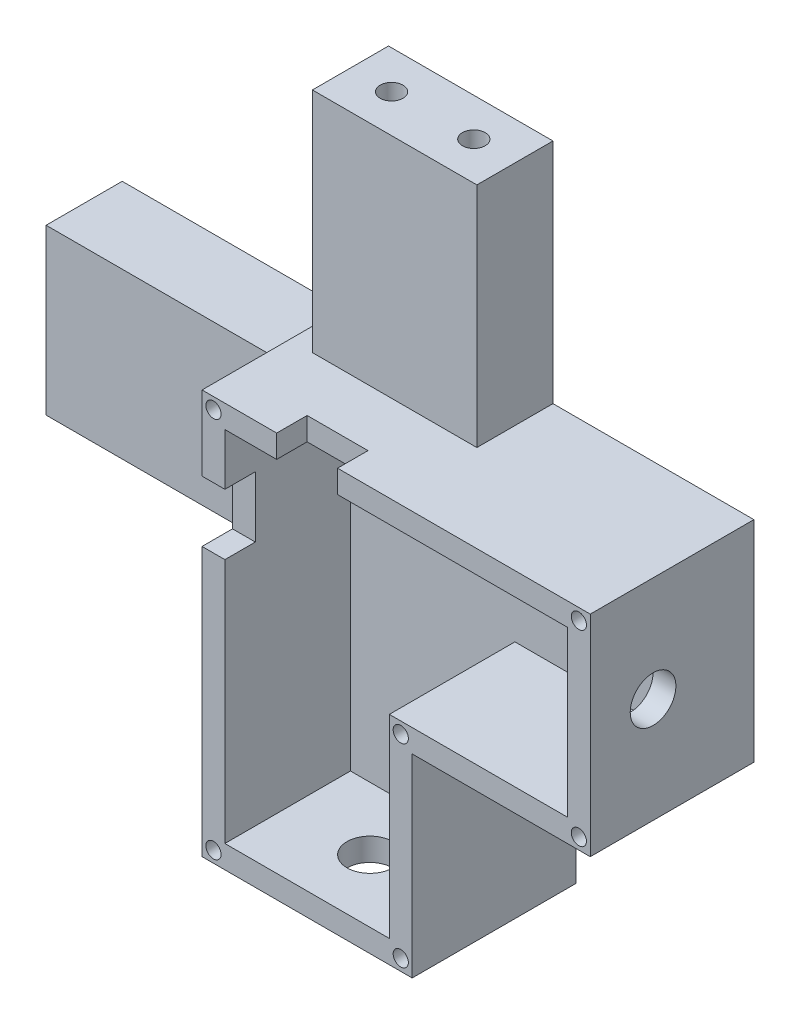
SolidWorks part; units mm, degrees
ref_plane "Plan de face" through (0, 0, 0) normal (0, 0, 1) x (1, 0, 0)
ref_plane "Plan de dessus" through (0, 0, 0) normal (0, 1, 0) x (1, 0, 0)
ref_plane "Plan de droite" through (0, 0, 0) normal (1, 0, 0) x (0, 0, -1)
sketch "Esquisse1" plane through (0, 0, 0) normal (0, 0, 1) x (1, 0, 0)
  line L1 (0, 0) -> (-80, 0)
  line L2 (0, 0) -> (0, 21.61)
  line L3 (0, 21.61) -> (-80, 21.61)
  line L4 (-80, 0) -> (-80, 21.61)
  line L5 (-45.01, 21.61) -> (-23.4, 21.61)
  line L6 (-45.01, 21.61) -> (-45.01, 54.5)
  line L7 (-45.01, 54.5) -> (-23.4, 54.5)
  line L8 (-23.4, 21.61) -> (-23.4, 54.5)
  line L9 (-45.01, 0) -> (-23.4, 0)
  line L10 (-45.01, 0) -> (-45.01, -25.5)
  line L11 (-45.01, -25.5) -> (-23.4, -25.5)
  line L12 (-23.4, 0) -> (-23.4, -25.5)
  line L13 (-48.01, 24.61) -> (3, 24.61)
  line L14 (-48.01, 24.61) -> (-48.01, -28.5)
  line L15 (-48.01, -28.5) -> (3, -28.5)
  line L16 (3, 24.61) -> (3, -28.5)
  line L17 (-20.4, -3) -> (3, -3)
  line L18 (-20.4, -3) -> (-20.4, -28.5)
  line L19 (-20.4, -28.5) -> (3, -28.5)
  line L20 (3, -3) -> (3, -28.5)
  dimension "D1" = 80
  dimension "D2" = 21.61
  dimension "D3" = 34.99
  dimension "D4" = 21.61
  dimension "D5" = 32.89
  dimension "D6" = 25.5
  dimension "D7" = 21.61
  dimension "D8" = 3
  dimension "D9" = 3
  dimension "D10" = 3
  dimension "D11" = 3
  dimension "D12" = 3
  dimension "D13" = 3
extrude "Boss.-Extru.1" add sketch "Esquisse1" along normal blind 26.5 contours L14 L3 L4 L1 | L3 L14 L1 L2 | L13 L14 L3 L6 | L13 L6 L3 L8 | L6 L13 L8 L7 | L18 L17 L16 L13 L8 L3 L2 L1 L12 L11 L10 L14 L15 | L12 L1 L10 L11
sketch "Esquisse2" plane through (0, 0, 26.5) normal (0, 0, 1) x (1, 0, 0)
  line L0 (-23.4, 24.61) -> (3, 24.61) construction
  line L1 (-45.01, 21.61) -> (0, 21.61)
  line L2 (-45.01, 21.61) -> (-45.01, 0)
  line L3 (-45.01, 0) -> (0, 0)
  line L4 (0, 21.61) -> (0, 0)
  line L5 (-45.01, 0) -> (-23.4, 0)
  line L6 (-45.01, 0) -> (-45.01, -25.5)
  line L7 (-45.01, -25.5) -> (-23.4, -25.5)
  line L8 (-23.4, 0) -> (-23.4, -25.5)
  line L9 (3, 24.61) -> (3, -3) construction
  line L10 (-20.4, -3) -> (-20.4, -28.5) construction
  line L11 (-48.01, -28.5) -> (-20.4, -28.5) construction
  line L12 (-48.01, 0) -> (-48.01, -28.5) construction
  dimension "D1" = 3
  dimension "D2" = 3
  dimension "D3" = 3
  dimension "D4" = 3
  dimension "D5" = 3
extrude "Enlèv. mat.-Extru.1" cut sketch "Esquisse2" against normal blind 21.5 contours L8 L3 L6 L7 | L4 L1 L2 L3
sketch "Esquisse3" plane through (0, 0, 26.5) normal (0, 0, 1) x (1, 0, 0)
  line L1 (-48.01, 24.61) -> (4.971, 24.61)
  line L2 (-48.01, 24.61) -> (-48.01, -33.1828)
  line L3 (-48.01, -33.1828) -> (4.971, -33.1828)
  line L4 (4.971, 24.61) -> (4.971, -33.1828)
extrude "Enlèv. mat.-Extru.2" cut sketch "Esquisse3" against normal blind 5
sketch "Esquisse4" plane through (0, 0, 21.5) normal (0, 0, 1) x (1, 0, 0)
  line L0 (-48.01, 24.61) -> (-45.01, 21.61)
  line L1 (3, 24.61) -> (0, 21.61)
  line L2 (3, -3) -> (0, 0)
  line L3 (-45.01, -25.5) -> (-48.01, -28.5)
  line L4 (-45.01, -25.5) -> (-45.01, 21.61) construction
  line L5 (-23.4, -25.5) -> (-20.4, -28.5)
  line L6 (-23.4, 0) -> (-20.4, -3)
  line L7 (-20.4, -3) -> (3, -3) construction
  circle A1 centre (-46.51, 23.11) radius 1
  circle A2 centre (1.5, 23.11) radius 1
  circle A3 centre (1.5, -1.5) radius 1
  circle A4 centre (-21.9, -1.5) radius 1
  circle A5 centre (-21.9, -27) radius 1
  circle A6 centre (-46.51, -27) radius 1
extrude "Enlèv. mat.-Extru.3" cut sketch "Esquisse4" against normal blind 5 contours L5 A5 | L5 A5 | L3 A6 | L3 A6 | L0 A1 | L0 A1 | L1 A2 | L2 A3 | L2 A3 | L6 A4 | L6 A4
sketch "Esquisse5" plane through (0, 0, 26.5) normal (0, 0, 1) x (1, 0, 0)
  line L1 (-80, 21.61) -> (-48.01, 21.61)
  line L2 (-80, 21.61) -> (-80, 0)
  line L3 (-80, 0) -> (-48.01, 0)
  line L4 (-48.01, 21.61) -> (-48.01, 0)
  line L5 (-23.4, 24.61) -> (-45.01, 24.61)
  line L6 (-23.4, 24.61) -> (-23.4, 54.5)
  line L7 (-23.4, 54.5) -> (-45.01, 54.5)
  line L8 (-45.01, 24.61) -> (-45.01, 54.5)
extrude "Enlèv. mat.-Extru.4" cut sketch "Esquisse5" against normal blind 16.5
sketch "Esquisse6" plane through (0, 0, 0) normal (-1, 0, 0) x (0, 0, 1)
  line L0 (5, 21.61) -> (21.5, 0)
  circle A0 centre (13.25, 10.805) radius 3
extrude "Enlèv. mat.-Extru.5" cut sketch "Esquisse6" against normal blind 16.5 contours L0 A0 | L0 A0
sketch "Esquisse7" plane through (0, -25.5, 0) normal (0, 1, 0) x (1, 0, 0)
  line L0 (-45.01, -5) -> (-23.4, -21.5)
  circle A0 centre (-34.205, -13.25) radius 3
extrude "Enlèv. mat.-Extru.6" cut sketch "Esquisse7" against normal blind 16.5 contours L0 A0 | L0 A0
sketch "Esquisse8" plane through (0, 24.61, 0) normal (0, 1, 0) x (1, 0, 0)
  line L0 (-34.205, -10) -> (-34.205, -21.5)
  line L1 (-45.01, -10) -> (-23.4, -10) construction
  line L2 (3, -21.5) -> (-48.01, -21.5) construction
  line L4 (-34.205, -21.5) -> (-30.205, -21.5)
  line L5 (-34.205, -21.5) -> (-34.205, -17.5)
  line L6 (-34.205, -17.5) -> (-30.205, -17.5)
  line L7 (-30.205, -21.5) -> (-30.205, -17.5)
  line L8 (-34.205, -17.5) -> (-38.205, -17.5)
  line L9 (-34.205, -17.5) -> (-34.205, -21.5)
  line L10 (-34.205, -21.5) -> (-38.205, -21.5)
  line L11 (-38.205, -17.5) -> (-38.205, -21.5)
  line M6 (-48.01, -21.5) -> (3, -21.5)
  dimension "D1" = 4
  dimension "D2" = 4
  dimension "D3" = 4
extrude "Enlèv. mat.-Extru.7" cut sketch "Esquisse8" against normal blind 16.5 contours L7 L6 L0 M6 | L8 L11 L0 M6
sketch "Esquisse9" plane through (-48.01, 0, 0) normal (-1, 0, 0) x (0, 0, 1)
  line L0 (10, 10.805) -> (21.5, 10.805)
  line L1 (10, 0) -> (10, 21.61) construction
  line L2 (21.5, 24.61) -> (21.5, -28.5) construction
  line L4 (21.5, 10.805) -> (17.5, 10.805)
  line L5 (21.5, 10.805) -> (21.5, 14.805)
  line L6 (21.5, 14.805) -> (17.5, 14.805)
  line L7 (17.5, 10.805) -> (17.5, 14.805)
  line L8 (21.5, 10.805) -> (17.5, 10.805)
  line L9 (21.5, 10.805) -> (21.5, 6.805)
  line L10 (21.5, 6.805) -> (17.5, 6.805)
  line L11 (17.5, 10.805) -> (17.5, 6.805)
  line M5 (21.5, -28.5) -> (21.5, 24.61)
  dimension "D1" = 4
  dimension "D2" = 4
  dimension "D3" = 4
extrude "Enlèv. mat.-Extru.8" cut sketch "Esquisse9" against normal blind 16.5 contours L0 L11 L10 M5 | L7 L0 L6 M5
sketch "Esquisse10" plane through (-80, 0, 0) normal (-1, 0, 0) x (0, 0, 1)
  line L0 (10, 21.61) -> (0, 10.805)
  line L1 (0, 0) -> (0, 21.61) construction
  line L2 (0, 10.805) -> (10, 0)
  circle A0 centre (5, 16.2075) radius 1.5
  circle A1 centre (5, 5.4025) radius 1.5
extrude "Enlèv. mat.-Extru.9" cut sketch "Esquisse10" against normal blind 5 contours L0 A0 | L0 A0 | L2 A1 | L2 A1
sketch "Esquisse11" plane through (0, 54.5, 0) normal (0, 1, 0) x (1, 0, 0)
  line L0 (-23.4, -10) -> (-34.205, 0)
  line L1 (-45.01, 0) -> (-23.4, 0) construction
  line L2 (-34.205, 0) -> (-45.01, -10)
  circle A0 centre (-28.8025, -5) radius 1.5
  circle A1 centre (-39.6075, -5) radius 1.5
extrude "Enlèv. mat.-Extru.10" cut sketch "Esquisse11" against normal blind 5 contours L0 A0 | L0 A0 | L2 A1 | L2 A1
